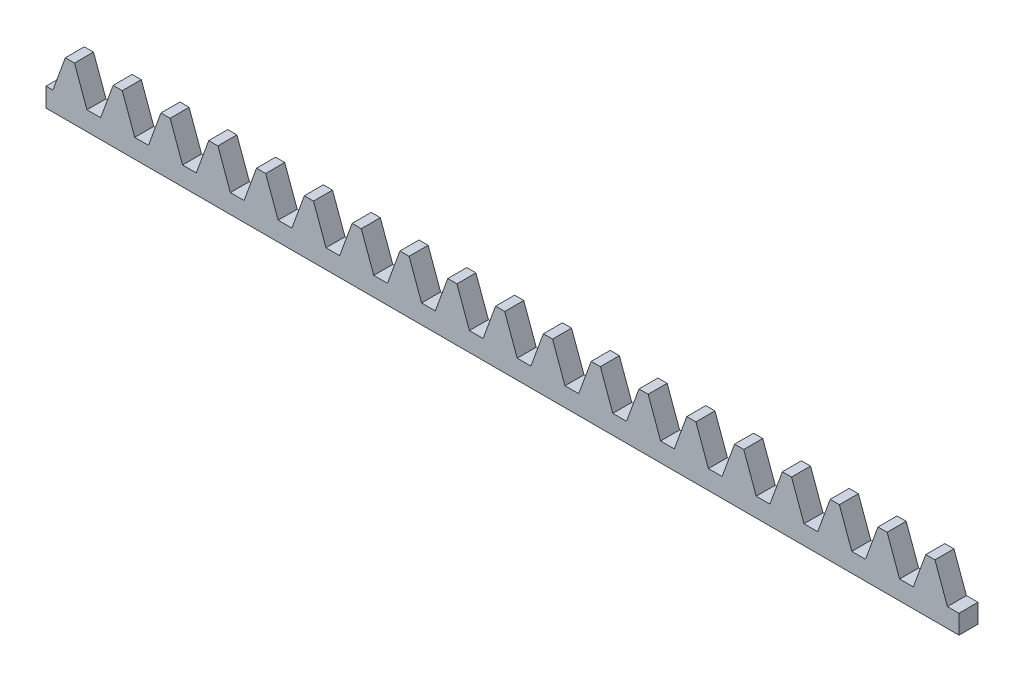
SolidWorks part; units mm, degrees
extrude "Blank" add sketch "BlankSke" against normal blind 3.175
sketch "BlankSke" plane through (0, 0, 0) normal (0, 0, 1) x (1, 0, 0)
  line L1 (0, 0) -> (152.4, 0)
  line L2 (0, 0) -> (0, 8.89)
  line L3 (0, 8.89) -> (152.4, 8.89)
  line L4 (152.4, 0) -> (152.4, 8.89)
  dimension "Length" = 152.4
  dimension "Blank_height" = 8.89
ref_plane "Plane1" through (0, 0, 0) normal (0, 0, 1) x (1, 0, 0)
ref_plane "Plane2" through (0, 0, 0) normal (0, 1, 0) x (1, 0, 0)
ref_plane "Plane3" through (0, 0, 0) normal (1, 0, 0) x (0, 0, -1)
sketch "HoldingSke" plane through (0, 0, 0) normal (0, 1, 0) x (1, 0, 0)
  line L0 (0, 0) -> (194.5753, -163.2681)
  line L1 (-15, 0) -> (100, 0) construction
  line L2 (0, 0) -> (-2.1039, 2.3779)
  line L3 (0, 0) -> (-11.863, 4.5341)
  line L4 (0, 0) -> (8.0624, 3.0949)
  line L5 (0, 0) -> (-23.7986, -8.8762)
  line L6 (0, 0) -> (-10.5278, -7.1032)
  line L9 (-71.009, 38.7566) -> (72.2002, 90.8805)
  line L10 (-76.2, 71.12) -> (-69.85, 71.12)
  line L11 (0, 0) -> (-3.175, 0)
  line L12 (-76.2, 101.6) -> (-76.0984, 101.6)
  line L13 (24.9733, 27.94) -> (52.9518, 28.4284)
  line L14 (24.9733, 27.94) -> (24.9746, 27.94)
  line L15 (24.9733, 27.94) -> (100.4006, 29.5858)
  circle A0 centre (0, 0) radius 19.05
  circle A1 centre (0, 0) radius 3.175
  circle A2 centre (0, 0) radius 12.7
  dimension "MPH" = 6.35
  dimension "Diameter" = 38.1
  dimension "Num_teeth" = 21
  dimension "Pitch" = 254
  dimension "Show_teeth" = 400
  dimension "Thickness" = 12.7
  dimension "Ap" = 20
  dimension "Pitch_height" = 6.35
  dimension "Width" = 3.175
  dimension "Backlash" = 0.1016
  dimension "Addendum_fac" = 1
  dimension "Dedendum_fac" = 1.25
  dimension "Clearance_fac" = 0.25
  dimension "Dedendum_add" = 0.0013
  dimension "Length" = 152.4
sketch "TooCutSkeIll" plane through (0, 0, 0) normal (0, 0, 1) x (1, 0, 0)
  line L0 (-3.1999, 8.8231) -> (-1.2965, 3.5937)
  line L1 (-0.6986, 3.175) -> (0.6986, 3.175)
  line L2 (1.2965, 3.5937) -> (3.1999, 8.8231)
  line L3 (152.4, 8.89) -> (0, 8.89) construction
  line L4 (0, 0) -> (0, 64.897) construction
  line L5 (-13.208, 6.35) -> (12.954, 6.35) construction
  line L6 (0, 0) -> (152.4, 0) construction
  line L7 (2.2997, 6.35) -> (2.2997, 48.7463) construction
  line L8 (-2.2997, 6.35) -> (-2.2997, 48.7463) construction
  line L9 (3.2953, 8.89) -> (3.2953, 8.9154)
  line L10 (-3.2953, 8.89) -> (-3.2953, 8.9154)
  line L11 (-3.2953, 8.9154) -> (3.2953, 8.9154)
  arc A0 (0.6986, 3.175) -> (1.2965, 3.5937) centre (0.6986, 3.8113) ccw
  arc A1 (-1.2965, 3.5937) -> (-0.6986, 3.175) centre (-0.6986, 3.8113) ccw
  arc A2 (3.2953, 8.89) -> (3.1999, 8.8231) centre (3.2953, 8.7884) ccw
  arc A3 (-3.1999, 8.8231) -> (-3.2953, 8.89) centre (-3.2953, 8.7884) ccw
  dimension "Pitch_height" = 6.35
  dimension "Addendum_plus" = 2.5654
  dimension "Pressure_angle" = 20
  dimension "Gap_width" = 4.5994
  dimension "Dedendum" = 3.175
extrude "ToothCutIll" [suppressed] cut sketch "TooCutSkeIll" against normal through all
sketch "TooCutSkeSim" plane through (0, 0, 0) normal (0, 0, 1) x (1, 0, 0)
  line L0 (1.1441, 3.175) -> (-1.1441, 3.175)
  line L1 (3.2334, 8.9154) -> (1.1441, 3.175)
  line L2 (0, 17.4625) -> (0, 53.467) construction
  line L3 (3.2334, 8.9154) -> (-3.2334, 8.9154)
  line L6 (-3.2334, 8.9154) -> (-1.1441, 3.175)
  line L9 (-2.2997, 6.35) -> (2.2997, 6.35) construction
  line L10 (0, 0) -> (152.4, 0) construction
  line L11 (2.2997, 6.35) -> (2.2997, 53.467) construction
  line L12 (-2.2997, 6.35) -> (-2.2997, 53.467) construction
  dimension "Pitch_height" = 6.35
  dimension "Addendum_plus" = 2.5654
  dimension "Pressure_angle" = 20
  dimension "Gap_width" = 4.5994
  dimension "Dedendum" = 3.175
extrude "ToothCutSim" cut sketch "TooCutSkeSim" against normal through all
pattern_linear "TeethCuts" count 20 spacing 7.9796 along (1, 0, 0) of "ToothCutIll", "ToothCutSim"
equation "' \"Pitch@HoldingSke\" = 4"
equation "' \"Num_teeth@HoldingSke\" = 12"
equation "' \"Ap@HoldingSke\" =  20"
equation "' \"Ap@HoldingSke\" = 20"
equation "' \"Width@HoldingSke\" = 0.25"
equation "' \"Show_teeth@HoldingSke\" = 500"
equation "' \"Backlash@HoldingSke\" = 0.009"
equation "' \"Addendum_fac@HoldingSke\" = 1.0"
equation "' \"Dedendum_fac@HoldingSke\" = 1.25"
equation "' \"Dedendum_add@HoldingSke\" = 0.00005"
equation "' \"Clearance_fac@HoldingSke\" = 0.25"
equation "' \"Pitch_height@HoldingSke\" = 1"
equation "' \"Length@HoldingSke\" = 4.71"
equation "\"MPH@HoldingSke\" = \"Dedendum_fac@HoldingSke\" / \"Pitch@HoldingSke\" + 2 * \"Dedendum_add@HoldingSke\" + 0.002"
equation "\"MPH@HoldingSke\" = ((sgn( \"MPH@HoldingSke\" - \"Pitch_height@HoldingSke\")+1)*( \"MPH@HoldingSke\" - \"Pitch_height@HoldingSke\"))/2 + \"Pitch_height@HoldingSke\""
equation "\"Blank_height@BlankSke\" = \"Pitch_height@HoldingSke\" + \"Addendum_fac@HoldingSke\"  / \"Pitch@HoldingSke\" "
equation "\"Length@BlankSke\" =  \"Length@HoldingSke\""
equation "\"Face_width@Blank\" = \"Width@HoldingSke\""
equation "\"Pressure_angle@TooCutSkeIll\" = \"Ap@HoldingSke\""
equation "\"Addendum_plus@TooCutSkeIll\" =  \"Addendum_fac@HoldingSke\"  / \"Pitch@HoldingSke\" + 0.001"
equation "\"Dedendum@TooCutSkeIll\" = \"Dedendum_fac@HoldingSke\"  / \"Pitch@HoldingSke\""
equation "\"Pitch_height@TooCutSkeIll\" =  \"MPH@HoldingSke\""
equation "\"Gap_width@TooCutSkeIll\" = 3.14159265 / 2 / \"Pitch@HoldingSke\" + 6 * \"Backlash@HoldingSke\""
equation "\"Pressure_angle@TooCutSkeSim\" = \"Ap@HoldingSke\""
equation "\"Addendum_plus@TooCutSkeSim\" =  \"Addendum_fac@HoldingSke\"  / \"Pitch@HoldingSke\" + 0.001"
equation "\"Dedendum@TooCutSkeSim\" = \"Dedendum_fac@HoldingSke\"  / \"Pitch@HoldingSke\""
equation "\"Pitch_height@TooCutSkeSim\" =  \"MPH@HoldingSke\""
equation "\"Gap_width@TooCutSkeSim\" = 3.14159265 / 2 / \"Pitch@HoldingSke\" + 6 * \"Backlash@HoldingSke\""
equation "\"Root_fillet@TooCutSkeIll\" = \"Clearance_fac@HoldingSke\" / \"Pitch@HoldingSke\" + \"Dedendum_add@HoldingSke\""
equation "\"Break_rad@TooCutSkeIll\" = 0.02 / \"Pitch@HoldingSke\" * 2"
equation "\"Linear_pitch@TeethCuts\" = 3.14159265 / \"Pitch@HoldingSke\""
equation "\"Num_teeth@HoldingSke\" = int( ( \"Length@HoldingSke\" + 0 ) / (3.14159265 / \"Pitch@HoldingSke\")) + 0.9999  + 1"
equation " \"Num_teeth@TeethCuts\" = int( \"Show_teeth@HoldingSke\" ) + 1"
equation " \"Num_teeth@TeethCuts\" = ((sgn( \"Num_teeth@TeethCuts\" - \"Num_teeth@HoldingSke\" )-1)*( \"Num_teeth@TeethCuts\" - \"Num_teeth@HoldingSke\" ))/-2+ \"Num_teeth@HoldingSke\""
equation " \"Num_teeth@TeethCuts\" = ((sgn( \"Num_teeth@TeethCuts\" - 2.0)+1)*( \"Num_teeth@TeethCuts\" - 2.0))/2 +2.0"
